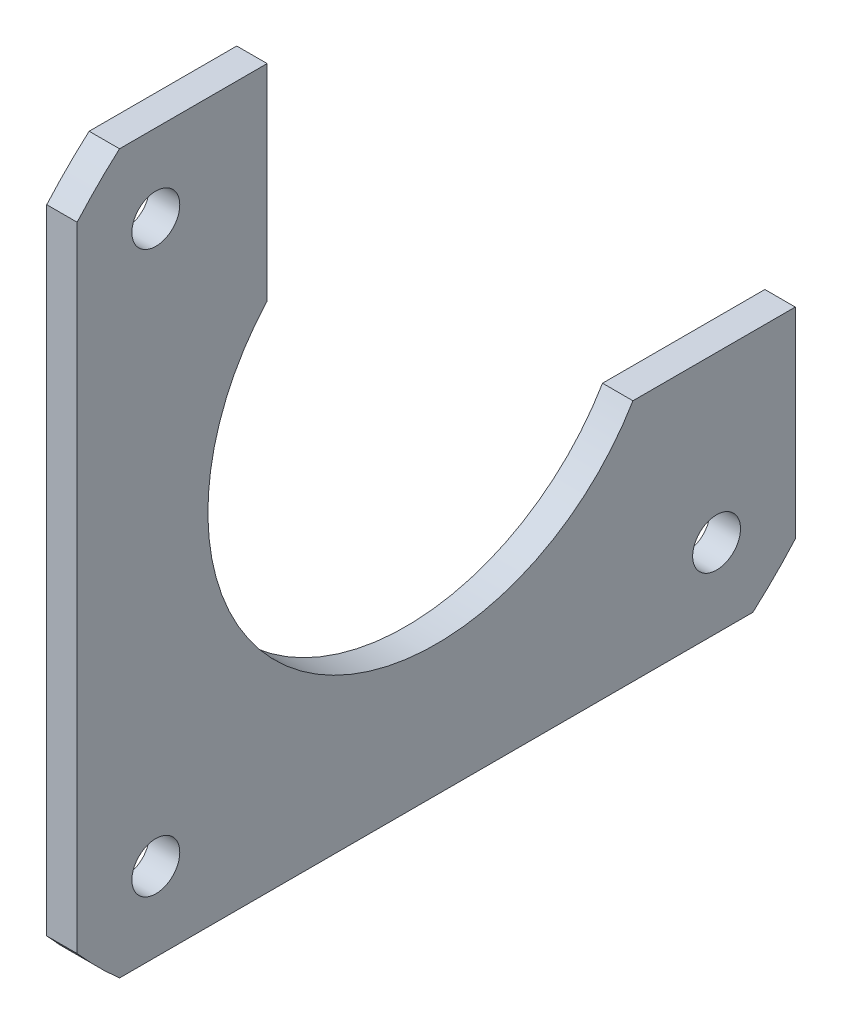
SolidWorks part; units mm, degrees
material "AISI 1020"
ref_plane "Front Plane" through (0, 0, 0) normal (0, 0, 1) x (1, 0, 0)
ref_plane "Top Plane" through (0, 0, 0) normal (0, 1, 0) x (1, 0, 0)
ref_plane "Right Plane" through (0, 0, 0) normal (1, 0, 0) x (0, 0, -1)
sketch "Sketch1" plane through (0, 0, 0) normal (1, 0, 0) x (0, 0, -1)
  line L0 (-30, 26.4575) -> (-30, -26.4575)
  line L5 (-30, 30) -> (30, 30) construction
  line L6 (-30, 30) -> (-30, -30) construction
  line L7 (-30, -30) -> (30, -30) construction
  line L8 (30, 30) -> (30, -30) construction
  line L9 (-30, 30) -> (30, -30) construction
  line L10 (-30, -30) -> (30, 30) construction
  line L11 (-26.4575, -30) -> (26.4575, -30)
  line L12 (30, -26.4575) -> (30, 26.4575)
  line L13 (26.4575, 30) -> (-26.4575, 30)
  line L14 (-20.75, -23.425) -> (20.75, -23.425) construction
  line L15 (23.425, -20.75) -> (23.425, 20.75) construction
  line L16 (20.75, 23.425) -> (-20.75, 23.425) construction
  line L17 (-23.425, 20.75) -> (-23.425, -20.75) construction
  line L18 (0, 23.425) -> (0, -23.425) construction
  arc A1 (-30, -26.4575) -> (-26.4575, -30) centre (0, 0) ccw
  arc A2 (-26.4575, 30) -> (-30, 26.4575) centre (0, 0) ccw
  arc A3 (30, 26.4575) -> (26.4575, 30) centre (0, 0) ccw
  arc A4 (26.4575, -30) -> (30, -26.4575) centre (0, 0) ccw
  circle A5 centre (0, 0) radius 19.075
  circle A6 centre (-23.425, -23.425) radius 2.675
  circle A7 centre (23.425, -23.425) radius 2.675
  circle A8 centre (23.425, 23.425) radius 2.675
  circle A9 centre (-23.425, 23.425) radius 2.675
  dimension "D1" = 80
  dimension "D4" = 38.15
  dimension "D5" = 5.35
  dimension "D2" = 90
  dimension "D3" = 60
  dimension "D6" = 41.5
  dimension "D7" = 41.5
extrude "Boss-Extrude1" add sketch "Sketch1" along normal blind 2.54
sketch "Sketch2" plane through (2.54, 0, 0) normal (1, 0, 0) x (0, 0, -1)
  circle A0 centre (23.425, 23.425) radius 2.675 construction
  circle A1 centre (23.425, -23.425) radius 2.675 construction
  circle A2 centre (-23.425, -23.425) radius 2.675 construction
  circle A3 centre (-23.425, 23.425) radius 2.675 construction
  circle A4 centre (-23.425, -23.425) radius 2.675
  circle A5 centre (23.425, 23.425) radius 2.675
  circle A6 centre (23.425, -23.425) radius 2.675
  circle A7 centre (-23.425, 23.425) radius 2.675
  circle A8 centre (-23.425, 23.425) radius 2
  circle A9 centre (-23.425, -23.425) radius 2
  circle A10 centre (23.425, -23.425) radius 2
  circle A11 centre (23.425, 23.425) radius 2
  dimension "D1" = 4
extrude "Boss-Extrude2" add sketch "Sketch2" against normal up to surface (2.54 mm away) up to face at (0, 0, 0)
sketch "Sketch3" plane through (2.54, 0, 0) normal (1, 0, 0) x (0, 0, -1)
  line L0 (-14.125, 30) -> (-14.125, 12.8195)
  line L1 (26.4575, 30) -> (-26.4575, 30) construction
  line L2 (16.4363, -9.68) -> (30, -9.68)
  line L3 (30, -26.4575) -> (30, 26.4575) construction
  line L4 (-26.4575, -30) -> (26.4575, -30) construction
  line L5 (-30, 26.4575) -> (-30, -26.4575) construction
  line L6 (-14.125, 12.8195) -> (16.4363, -9.68)
  line L7 (30, -9.68) -> (30, 30)
  line L8 (30, 30) -> (-14.125, 30)
  circle A0 centre (0, 0) radius 19.075 construction
  dimension "D1" = 20.32
  dimension "D2" = 15.875
extrude "Cut-Extrude1" cut sketch "Sketch3" against normal through all
